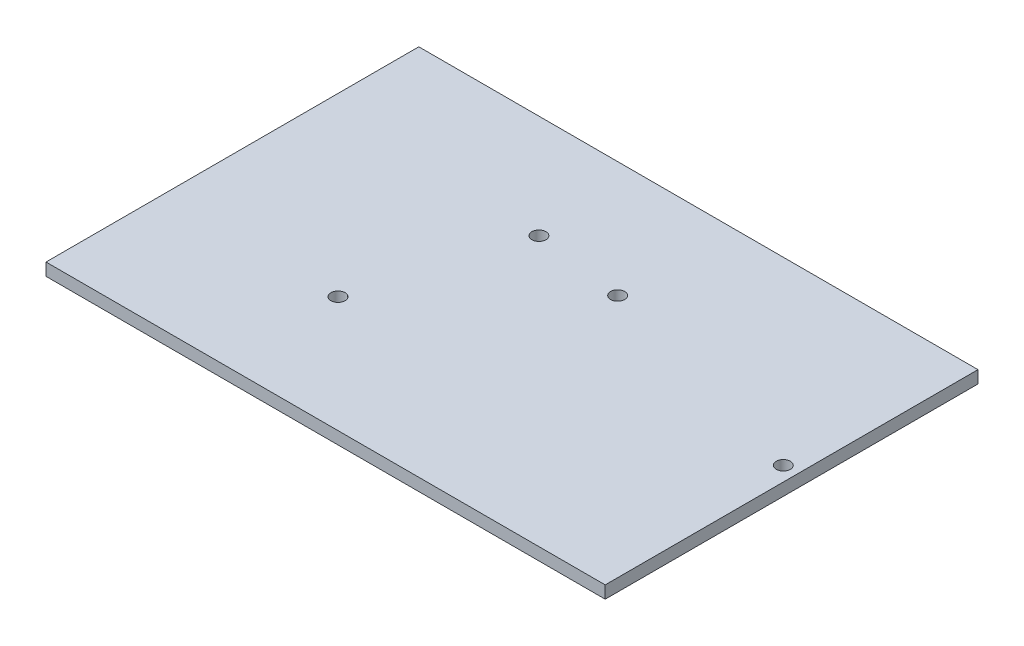
SolidWorks part; units mm, degrees
ref_plane "Ebene vorne" through (0, 0, 0) normal (0, 0, 1) x (1, 0, 0)
ref_plane "Ebene oben" through (0, 0, 0) normal (0, 1, 0) x (1, 0, 0)
ref_plane "Ebene rechts" through (0, 0, 0) normal (1, 0, 0) x (0, 0, -1)
sketch "Skizze1" plane through (0, 0, 0) normal (0, 1, 0) x (1, 0, 0)
  line L1 (67.5, -45) -> (-67.5, -45)
  line L2 (67.5, -45) -> (67.5, 45)
  line L3 (67.5, 45) -> (-67.5, 45)
  line L4 (-67.5, -45) -> (-67.5, 45)
  line L5 (67.5, -45) -> (-67.5, 45) construction
  line L6 (67.5, 45) -> (-67.5, -45) construction
  point P0 (0, 0)
  dimension "D1" = 90
  dimension "D2" = 135
extrude "Aufsatz-Linear austragen1" add sketch "Skizze1" along normal blind 3
sketch "Skizze2" plane through (0, 3, 0) normal (0, 1, 0) x (1, 0, 0)
  line L0 (67.5, 45) -> (-67.5, 45) construction
  line L1 (67.5, -45) -> (67.5, 45) construction
  circle A0 centre (-13.5, 20) radius 1.7
  circle A1 centre (8.5, 17) radius 1.7
  circle A2 centre (-25, -17) radius 1.7
  circle A3 centre (64, 1.5) radius 1.7
  dimension "D1" = 62
  dimension "D9" = 3.4
  dimension "D2" = 55.5
  dimension "D3" = 22
  dimension "D4" = 11.5
  dimension "D5" = 25
  dimension "D6" = 3
  dimension "D7" = 18.5
  dimension "D8" = 3.5
extrude "Schnitt-Linear austragen2" cut sketch "Skizze2" against normal through all
